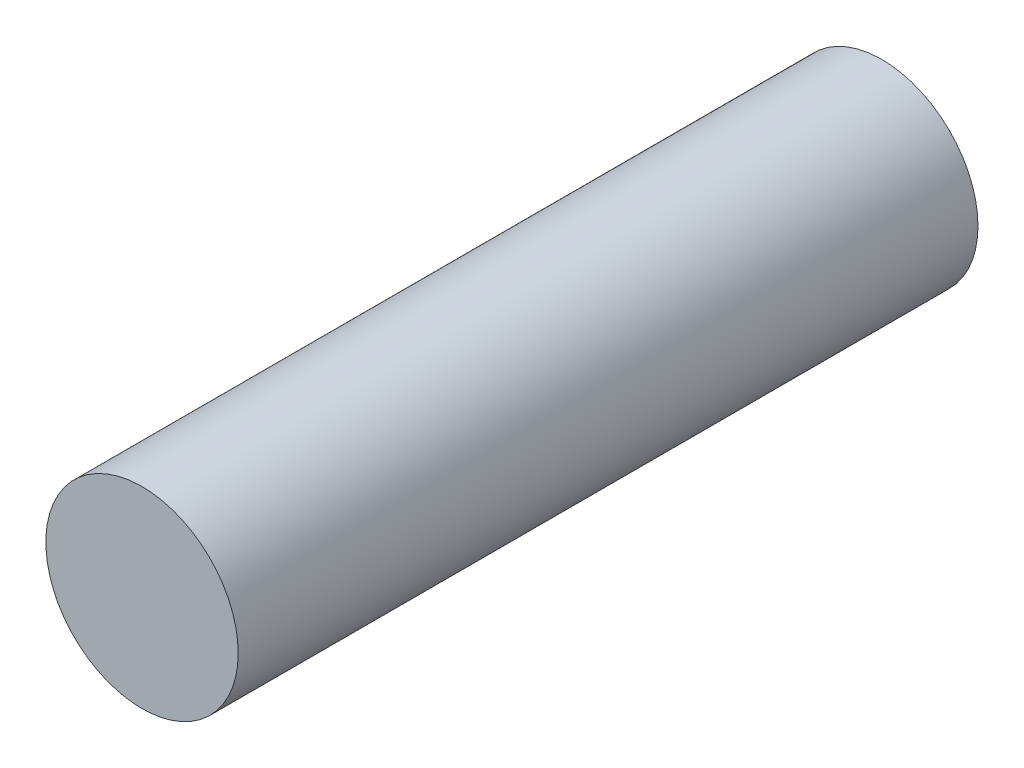
SolidWorks part; units mm, degrees
ref_plane "前视基准面" through (0, 0, 0) normal (0, 0, 1) x (1, 0, 0)
ref_plane "上视基准面" through (0, 0, 0) normal (0, 1, 0) x (1, 0, 0)
ref_plane "右视基准面" through (0, 0, 0) normal (1, 0, 0) x (0, 0, -1)
sketch "草图1" plane through (0, 0, 0) normal (0, 0, 1) x (1, 0, 0)
  circle A0 centre (0, 0) radius 13
  circle A1 centre (0, 0) radius 10
  dimension "D1" = 26
  dimension "D2" = 20
extrude "凸台-拉伸1" add sketch "草图1" along normal blind 100
sketch "草图2" plane through (0, 0, 100) normal (0, 0, 1) x (1, 0, 0)
  circle A0 centre (0, 0) radius 13
extrude "凸台-拉伸2" add sketch "草图2" against normal blind 5
sketch "草图3" plane through (0, 0, 0) normal (0, 0, -1) x (-1, 0, 0)
  circle A0 centre (0, 0) radius 11.5 construction
  circle A1 centre (0, 11.5) radius 1
  circle A2 centre (11.5, 0) radius 1
  circle A3 centre (0, -11.5) radius 1
  circle A4 centre (-11.5, 0) radius 1
  dimension "D1" = 23
  dimension "D2" = 2
  dimension "D3" = 4
extrude "切除-拉伸1" cut sketch "草图3" against normal blind 5
